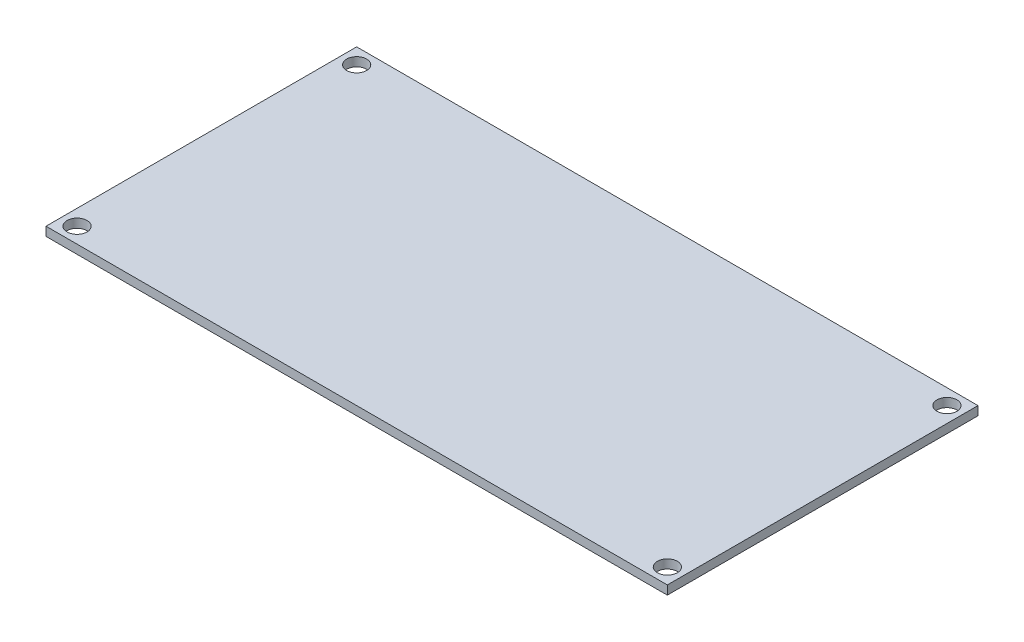
SolidWorks part; units mm, degrees
ref_plane "Front Plane" through (0, 0, 0) normal (0, 0, 1) x (1, 0, 0)
ref_plane "Top Plane" through (0, 0, 0) normal (0, 1, 0) x (1, 0, 0)
ref_plane "Right Plane" through (0, 0, 0) normal (1, 0, 0) x (0, 0, -1)
sketch "Sketch1" plane through (0, 0, 0) normal (0, 1, 0) x (1, 0, 0)
  line L1 (-50.8, -25.4) -> (50.8, -25.4)
  line L2 (-50.8, -25.4) -> (-50.8, 25.4)
  line L3 (-50.8, 25.4) -> (50.8, 25.4)
  line L4 (50.8, -25.4) -> (50.8, 25.4)
  line L5 (-50.8, -25.4) -> (50.8, 25.4) construction
  line L6 (-50.8, 25.4) -> (50.8, -25.4) construction
  point P0 (0, 0)
  dimension "D1" = 101.6
  dimension "D2" = 50.8
extrude "Boss-Extrude1" add sketch "Sketch1" along normal blind 1.4478
sketch "Sketch2" plane through (0, 1.4478, 0) normal (0, 1, 0) x (1, 0, 0)
  line L0 (-50.8, 25.4) -> (-50.8, -25.4) construction
  line L1 (-48.26, -22.86) -> (48.26, -22.86) construction
  line L2 (-48.26, -22.86) -> (-48.26, 22.86) construction
  line L3 (-48.26, 22.86) -> (48.26, 22.86) construction
  line L4 (48.26, -22.86) -> (48.26, 22.86) construction
  line L5 (-48.26, -22.86) -> (48.26, 22.86) construction
  line L6 (-48.26, 22.86) -> (48.26, -22.86) construction
  line L7 (50.8, 25.4) -> (-50.8, 25.4) construction
  circle A0 centre (-48.26, 22.86) radius 1.6319
  circle A1 centre (-48.26, -22.86) radius 1.6319
  circle A2 centre (48.26, -22.86) radius 1.6319
  circle A3 centre (48.26, 22.86) radius 1.6319
  point P0 (0, 0)
  dimension "D3" = 3.2639
  dimension "D1" = 2.54
  dimension "D2" = 2.54
extrude "Cut-Extrude1" cut sketch "Sketch2" against normal through all
